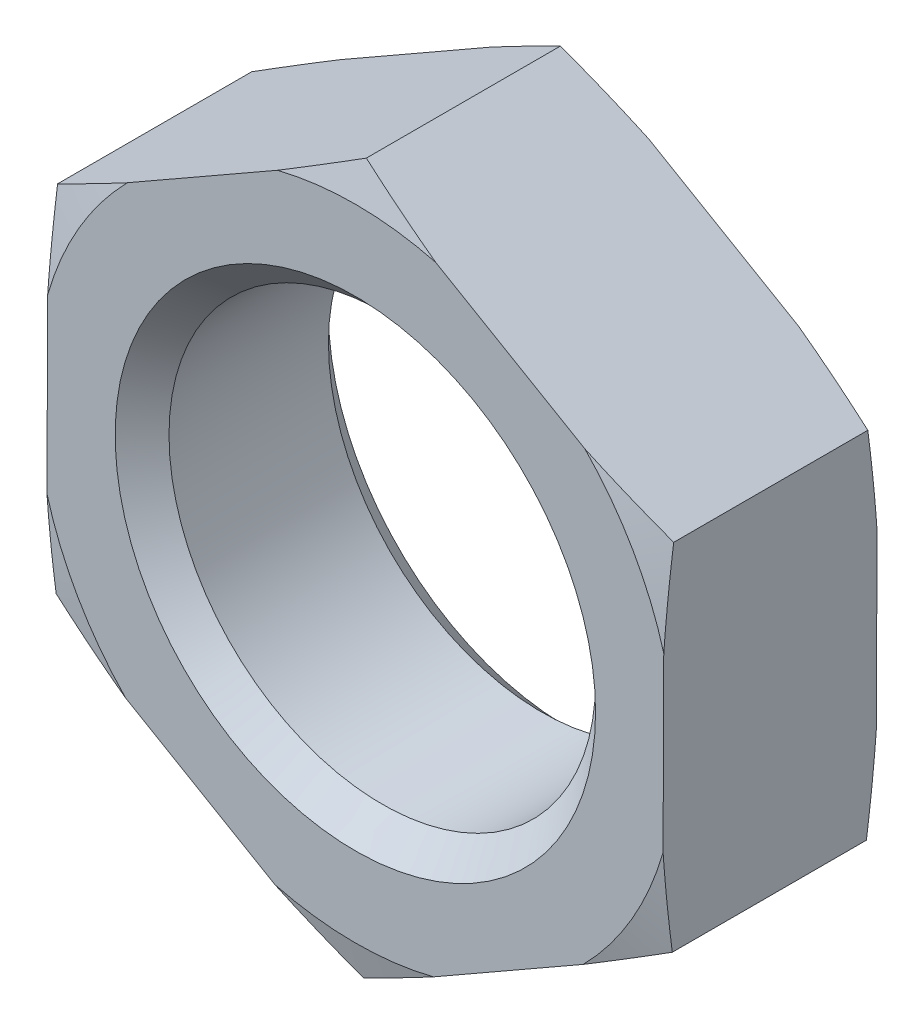
SolidWorks part; units mm, degrees
extrude "基体-拉伸" add sketch "草图1" along normal blind 7
sketch "草图1" plane through (0, 0, 0) normal (0, 0, 1) x (1, 0, 0)
  line L0 (-26.8088, 0) -> (37.1748, 0) construction
  line L1 (0, 25.0215) -> (0, -25.0215) construction
  line L3 (0.0459, 11.6749) -> (-10.0878, 5.8772)
  line L4 (-10.0878, 5.8772) -> (-10.1337, -5.7977)
  line L5 (-10.1337, -5.7977) -> (-0.0459, -11.6749)
  line L6 (-0.0459, -11.6749) -> (10.0878, -5.8772)
  line L7 (10.0878, -5.8772) -> (10.1337, 5.7977)
  line L8 (10.1337, 5.7977) -> (0.0459, 11.6749)
  circle A0 centre (0, 0) radius 10.1108 construction
  circle A1 centre (0, 0) radius 7
  dimension "D" = 14
  dimension "e" = 23.35
cosmetic thread "装饰螺纹线1"
chamfer "倒角1" distance 0.8833 angle 45 2 edges at (7, 0, 0) (7, 0, 7)
ref_plane "基准面1" through (0, 0, 0) normal (0, 0, 1) x (1, 0, 0)
ref_plane "基准面2" through (0, 0, 0) normal (0, 1, 0) x (1, 0, 0)
ref_plane "基准面3" through (0, 0, 0) normal (1, 0, 0) x (0, 0, -1)
sketch "尺寸草图" plane through (0, 0, 0) normal (0, 0, 1) x (1, 0, 0)
  line L0 (0, 0) -> (24.1005, 0)
  line L1 (0, 0) -> (15.1, 0)
  line L2 (46.8781, 0) -> (66.4781, 0)
  line L3 (-13.3333, 0) -> (0, 0)
  point P3 (14, 0)
  point P4 (2.5, 0)
  point P5 (23.35, 0)
  point P6 (7, 0)
  point P7 (7.3, 0)
  point P8 (21, 0)
  dimension "D" = 14
  dimension "e" = 23.35
  dimension "P" = 2.5
  dimension "m" = 7
  dimension "mw" = 7.3
  dimension "s" = 21
  dimension "da" = 15.1
  dimension "dw" = 19.6
  dimension "D1" = 13.3333
sketch "草图2" plane through (0, 0, 0) normal (0, 0, -1) x (-1, 0, 0)
  circle A0 centre (0, 0) radius 10.5
  circle A1 centre (0, 0) radius 7 construction
  dimension "s" = 21
extrude "切除-拉伸1" cut sketch "草图2" against normal through all draft 75 flip side to cut
sketch "草图3" plane through (0, 0, 7) normal (0, 0, 1) x (1, 0, 0)
  circle A0 centre (0, 0) radius 10.5
  dimension "D1" = 21
extrude "切除-拉伸2" cut sketch "草图3" against normal through all draft 75 flip side to cut
equation "\"e@草图1\" = \"e@尺寸草图\""
equation "\"D1@尺寸草图\" = \"D@尺寸草图\" / 1.05"
equation "\"D@草图1\" = \"D@尺寸草图\""
equation "\"m@基体-拉伸\" = \"m@尺寸草图\""
equation "\"D1@草图3\" = \"s@尺寸草图\""
equation "\"s@草图2\" = \"s@尺寸草图\""
equation "\"D2@装饰螺纹线1\" = 1.05 * \"D1@尺寸草图\""
equation "\"D1@倒角1\" =  ( \"da@尺寸草图\" - \"D1@尺寸草图\" )  / 2"
